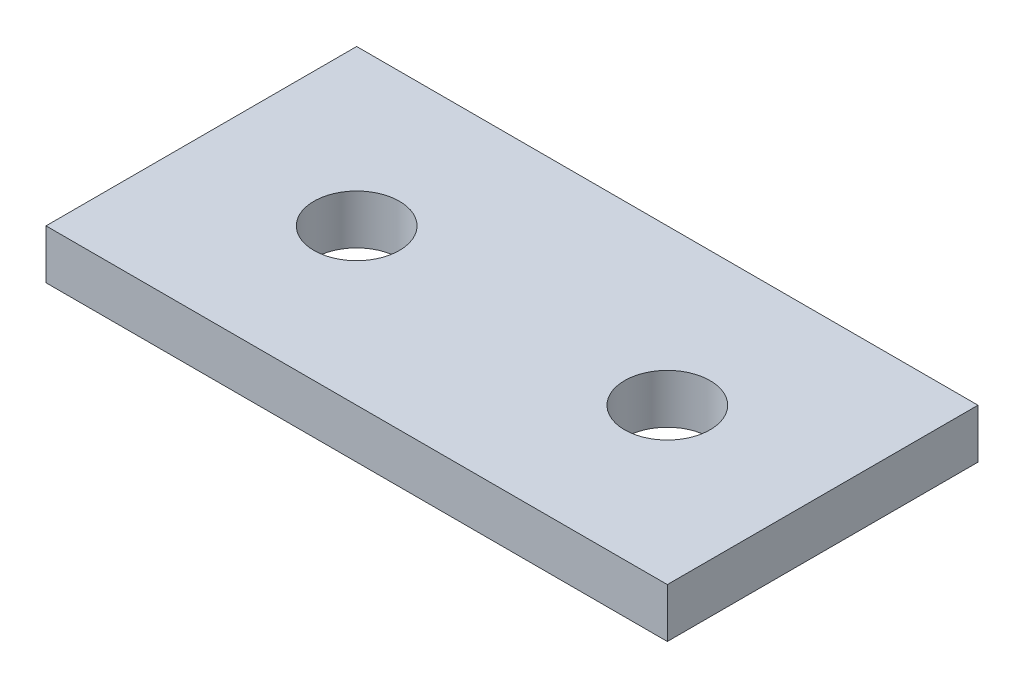
SolidWorks part; units mm, degrees
ref_plane "Front Plane" through (0, 0, 0) normal (0, 0, 1) x (1, 0, 0)
ref_plane "Top Plane" through (0, 0, 0) normal (0, 1, 0) x (1, 0, 0)
ref_plane "Right Plane" through (0, 0, 0) normal (1, 0, 0) x (0, 0, -1)
sketch "Sketch1" plane through (0, 0, 0) normal (0, 1, 0) x (1, 0, 0)
  line L0 (0, 0) -> (-10, 0) construction
  line L1 (-20, -10) -> (20, -10)
  line L2 (-20, -10) -> (-20, 10)
  line L3 (-20, 10) -> (20, 10)
  line L4 (20, -10) -> (20, 10)
  line L5 (-20, -10) -> (20, 10) construction
  line L6 (-20, 10) -> (20, -10) construction
  line L7 (0, 0) -> (10, 0) construction
  circle A0 centre (-10, 0) radius 2.75
  circle A1 centre (10, 0) radius 2.75
  point P0 (0, 0)
  dimension "D4" = 5.5
  dimension "D5" = 5.5
  dimension "D1" = 40
  dimension "D2" = 20
  dimension "D3" = 10
extrude "Boss-Extrude1" add sketch "Sketch1" along normal blind 3.175
